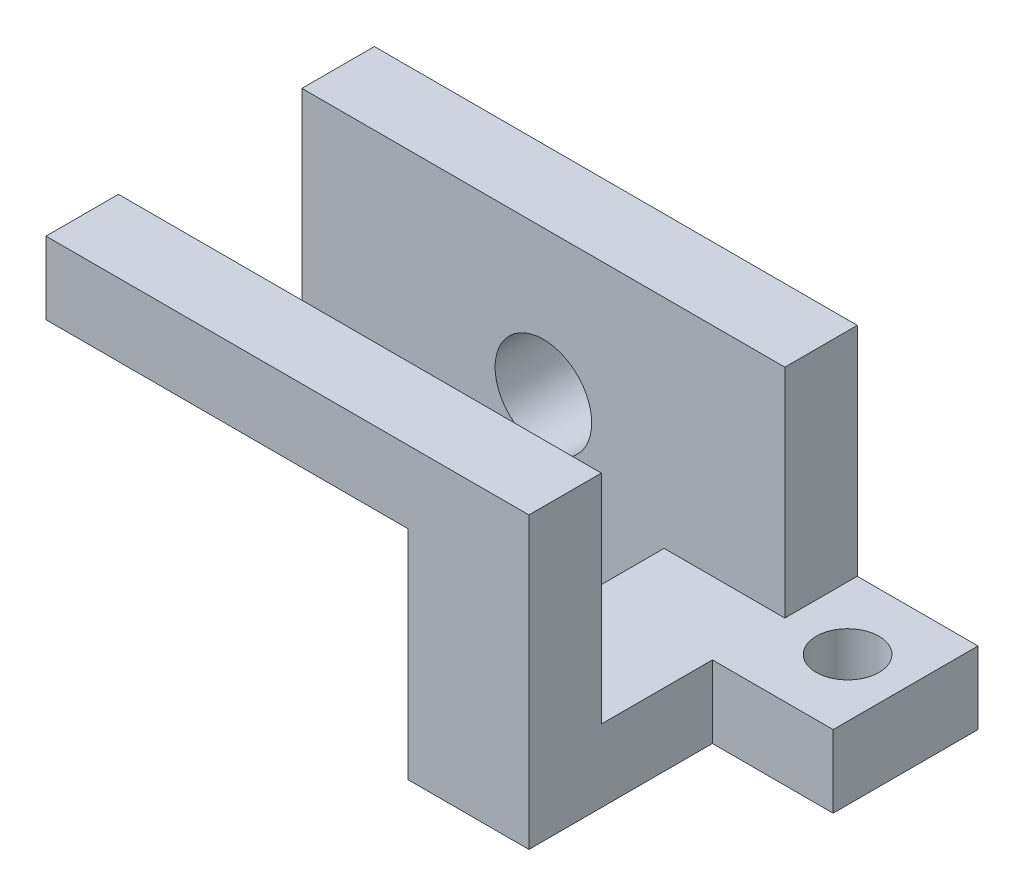
SolidWorks part; units mm, degrees
ref_plane "Front Plane" through (0, 0, 0) normal (0, 0, 1) x (1, 0, 0)
ref_plane "Top Plane" through (0, 0, 0) normal (0, 1, 0) x (1, 0, 0)
ref_plane "Right Plane" through (0, 0, 0) normal (1, 0, 0) x (0, 0, -1)
sketch "Sketch1" plane through (0, 0, 0) normal (0, 0, 1) x (1, 0, 0)
  line L1 (75, -30) -> (-50, -30)
  line L2 (75, -30) -> (75, 30)
  line L3 (75, 30) -> (-50, 30)
  line L4 (-50, -30) -> (-50, 30)
  point P0 (0, 0)
  point P6 (0, 0)
  point P7 (-50, 0)
  dimension "D1" = 125
  dimension "D2" = 60
  dimension "D3" = 50
extrude "Boss-Extrude1" add sketch "Sketch1" along normal blind 68 from offset 15 offset against normal yes
sketch "Sketch2" plane through (75, 0, 0) normal (1, 0, 0) x (0, 0, -1)
  line L6 (-53, 30) -> (15, 30) construction
  line L7 (-38, 30) -> (0, 30)
  line L8 (-38, 30) -> (-38, -15)
  line L9 (-38, -15) -> (0, -15)
  line L10 (0, 30) -> (0, -15)
  line L11 (-53, -30) -> (15, -30) construction
  line L12 (-53, -30) -> (-53, 30) construction
  dimension "D1" = 38
  dimension "D2" = 15
  dimension "D3" = 15
extrude "Cut-Extrude1" cut sketch "Sketch2" against normal through all
sketch "Sketch3" plane through (0, 30, 0) normal (0, 1, 0) x (1, 0, 0)
  line L0 (50, 15) -> (75, 15)
  line L15 (50, 15) -> (50, -15)
  line L18 (-50, 0) -> (-50, 15) construction
  line L19 (50, -15) -> (75, -15)
  line L20 (75, -38) -> (75, 0) construction
  line L21 (75, -15) -> (75, 15)
  line L22 (-50, 15) -> (75, 15) construction
  point P0 (50, 15)
  dimension "D1" = 30
  dimension "D4" = 100
extrude "Cut-Extrude2" cut sketch "Sketch3" against normal up to vertex (45 mm away)
sketch "Sketch4" plane through (0, 30, 0) normal (0, 1, 0) x (1, 0, 0)
  line L1 (75, -53) -> (50, -53)
  line L2 (75, -53) -> (75, -15)
  line L3 (75, -15) -> (50, -15)
  line L4 (50, -53) -> (50, -15)
  dimension "D1" = 38
  dimension "D2" = 25
extrude "Cut-Extrude3" cut sketch "Sketch4" against normal through all
sketch "Sketch5" plane through (0, 0, 53) normal (0, 0, 1) x (1, 0, 0)
  line L1 (-50, -30) -> (25, -30)
  line L2 (-50, -30) -> (-50, 15)
  line L3 (-50, 15) -> (25, 15)
  line L4 (25, -30) -> (25, 15)
  dimension "D1" = 75
  dimension "D2" = 45
extrude "Cut-Extrude4" cut sketch "Sketch5" against normal up to vertex
hole_wizard "Hole1" positions "Sketch7" profile "Sketch8" legacy end condition through all
sketch "Sketch7" plane through (0, -15, 0) normal (0, 1, 0) x (1, 0, 0)
  line L0 (75, -15) -> (75, 15) construction
  line L1 (75, 15) -> (50, 15) construction
  point P0 (63, 0)
  dimension "D1" = 12
  dimension "D2" = 15
sketch "Sketch8" plane through (63, -15, 0) normal (1, 0, 0) x (0, 0, 1)
  line L0 (0, 0) -> (0, 15)
  line L1 (0, 15) -> (6.5, 15)
  line L2 (6.5, 15) -> (6.5, 0)
  line L3 (6.5, 0) -> (0, 0)
  line L4 (0, 110) -> (0, -10) construction
  dimension "Diameter" = 13
  dimension "Depth" = 15
hole_wizard "Hole2" positions "Sketch9" profile "Sketch10" legacy end condition through all
sketch "Sketch9" plane through (0, 0, 0) normal (0, 0, 1) x (1, 0, 0)
  line L0 (-50, -30) -> (-50, 30) construction
  line L1 (-50, -30) -> (25, -30) construction
  point P0 (0, 0)
  dimension "D1" = 50
  dimension "D2" = 30
sketch "Sketch10" plane through (0, 0, 0) normal (1, 0, 0) x (0, -1, 0)
  line L0 (0, 0) -> (0, 15)
  line L1 (0, 15) -> (10, 15)
  line L2 (10, 15) -> (10, 0)
  line L3 (10, 0) -> (0, 0)
  line L4 (0, 110) -> (0, -10) construction
  dimension "Diameter" = 20
  dimension "Depth" = 15
